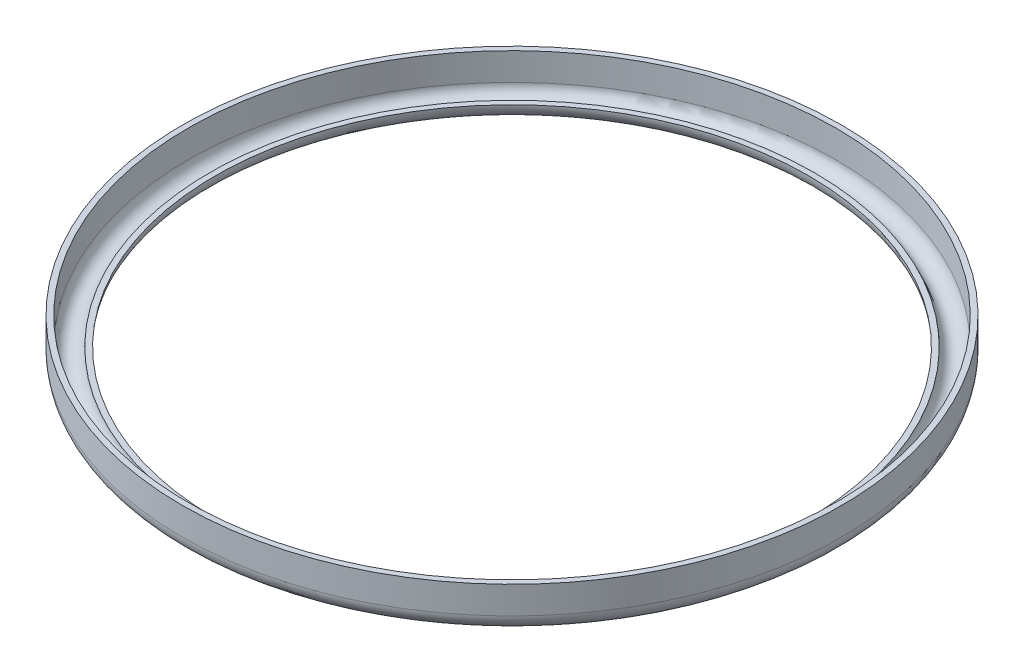
SolidWorks part; units mm, degrees
material "PC High Viscosity"
ref_plane "Front Plane" through (0, 0, 0) normal (1, 0, 0) x (0, 1, 0)
ref_plane "Top Plane" through (0, 0, 0) normal (0, 0, 1) x (0, 1, 0)
ref_plane "Right Plane" through (0, 0, 0) normal (0, 1, 0) x (-1, 0, 0)
sketch "Sketch1" plane through (0, 0, 0) normal (1, 0, 0) x (0, 1, 0)
  line L0 (0, 96.2202) -> (0, -67.1729) construction
  line L1 (-17.0549, 0) -> (12.3018, 0) construction
  line L2 (5, 60) -> (0, 60)
  line L3 (5, 59) -> (0, 59)
  line L4 (0, 55) -> (0, 54)
  line L5 (5, 60) -> (5, 59)
  arc A0 (0, 60) -> (0, 54) centre (0, 57) ccw
  arc A1 (0, 59) -> (0, 55) centre (0, 57) ccw
  dimension "D2" = 3
  dimension "D1" = 5
  dimension "D3" = 120
  dimension "D4" = 1
revolve "Revolve1" add sketch "Sketch1" angle 360 about L1
